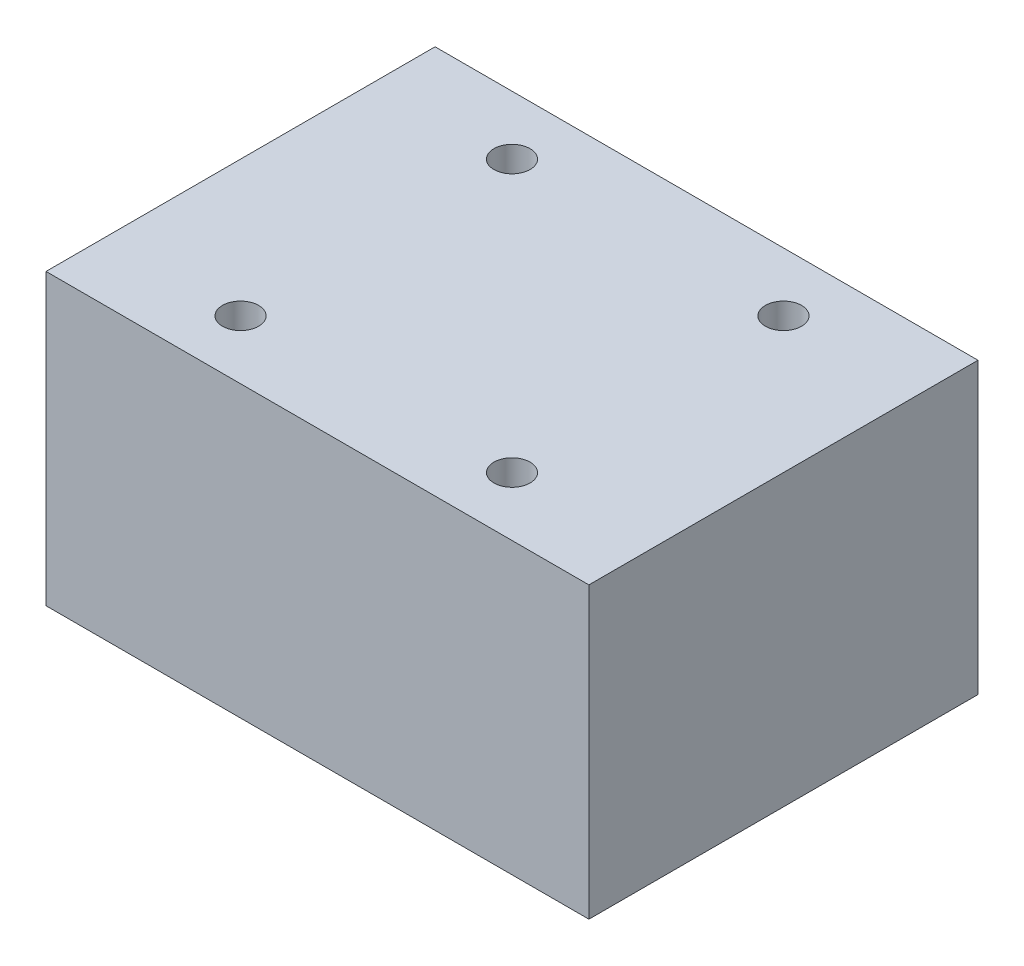
SolidWorks part; units mm, degrees
material "Ductile Iron"
ref_plane "Front Plane" through (0, 0, 0) normal (0, 0, 1) x (1, 0, 0)
ref_plane "Top Plane" through (0, 0, 0) normal (0, 1, 0) x (1, 0, 0)
ref_plane "Right Plane" through (0, 0, 0) normal (1, 0, 0) x (0, 0, -1)
sketch "Sketch1" plane through (0, 0, 0) normal (0, 1, 0) x (1, 0, 0)
  line L1 (-30, 21.5) -> (30, 21.5)
  line L2 (-30, 21.5) -> (-30, -21.5)
  line L3 (-30, -21.5) -> (30, -21.5)
  line L4 (30, 21.5) -> (30, -21.5)
  line L5 (-30, 21.5) -> (30, -21.5) construction
  line L6 (-30, -21.5) -> (30, 21.5) construction
  point P0 (0, 0)
  dimension "D1" = 43
  dimension "D2" = 60
extrude "Boss-Extrude1" add sketch "Sketch1" along normal blind 32
sketch "Sketch2" plane through (0, 32, 0) normal (0, 1, 0) x (1, 0, 0)
  line L1 (-15, 15) -> (15, 15) construction
  line L2 (-15, 15) -> (-15, -15) construction
  line L3 (-15, -15) -> (15, -15) construction
  line L4 (15, 15) -> (15, -15) construction
  line L5 (-15, 15) -> (15, -15) construction
  line L6 (-15, -15) -> (15, 15) construction
  point P0 (0, 0)
  point P7 (-15, 15)
  point P8 (-15, -15)
  point P9 (15, -15)
  point P10 (15, 15)
  dimension "D1" = 30
hole_wizard "Ø4.0mm Dowel Hole1" positions "3DSketch1" profile "Sketch3" hole size "Ø4.0" standard "IS" end condition through all
sketch3d "3DSketch1"
  point P0 (-15, 32, -15)
  point P3 (-15, 32, 15)
  point P6 (15, 32, 15)
  point P9 (15, 32, -15)
sketch "Sketch3" plane through (-15, 32, -15) normal (1, 0, 0) x (0, 0, 1)
  line L0 (0, 0) -> (0, 32)
  line L1 (0, 32) -> (2, 32)
  line L2 (2, 32) -> (2, 0)
  line L5 (2, 0) -> (0, 0)
  line L11 (0, -6.35) -> (0, 107.95) construction
  dimension "Thru Hole Dia." = 4
  dimension "Thru Hole Depth" = 32
